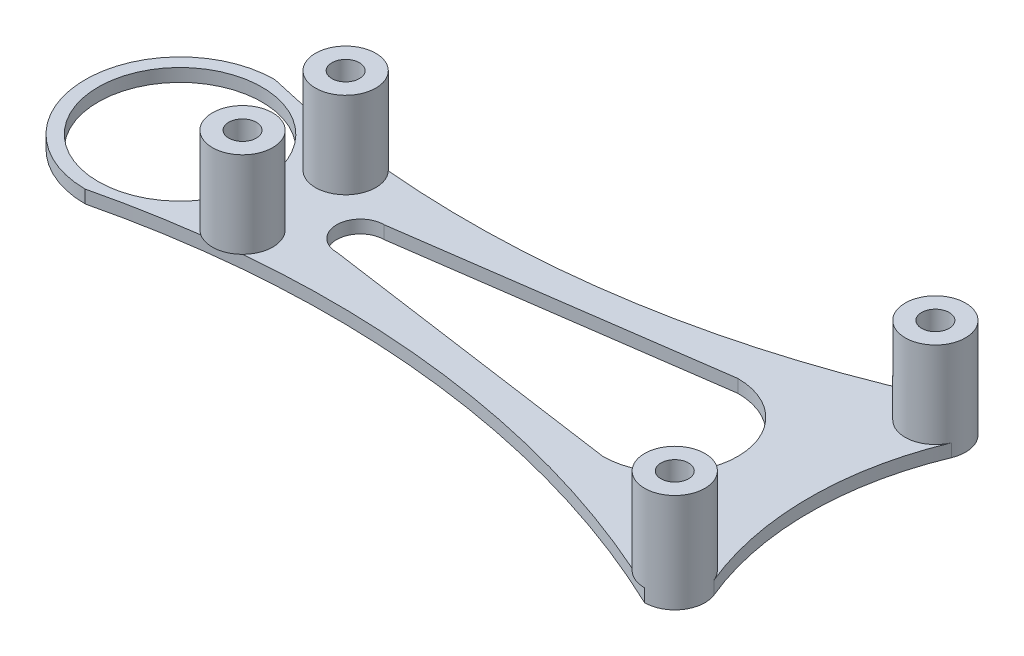
SolidWorks part; units mm, degrees
material "ABS"
ref_plane "Plano frontal" through (0, 0, 0) normal (0, 0, 1) x (1, 0, 0)
ref_plane "Plano superior" through (0, 0, 0) normal (0, 1, 0) x (1, 0, 0)
ref_plane "Plano direito" through (0, 0, 0) normal (1, 0, 0) x (0, 0, -1)
sketch "Esboço1" plane through (0, 0, 0) normal (0, 1, 0) x (1, 0, 0)
  line L0 (0, 43) -> (0, -43) construction
  line L1 (0, -43) -> (43, 0) construction
  line L2 (43, 0) -> (0, 43) construction
  line L3 (0, 43) -> (-43, 0) construction
  line L4 (-43, 0) -> (0, -43) construction
  line L5 (-43, 0) -> (43, 0) construction
  line L6 (0, 0) -> (-39.7268, 16.4554) construction
  line L7 (0, 0) -> (-39.7268, -16.4554) construction
  circle A0 centre (0, 0) radius 43 construction
  arc A1 (-33.2597, 13.7766) -> (-33.2597, -13.7766) centre (0, 0) ccw
  arc A2 (-109, 11) -> (-109, -11) centre (-109, 0) ccw
  circle A3 centre (-36.4932, 15.116) radius 1.6
  circle A4 centre (-36.4932, -15.116) radius 1.6
  arc A5 (-33.2597, 13.7766) -> (-36.4932, 18.616) centre (-36.4932, 15.116) ccw
  circle A6 centre (-95.79, 6) radius 1.6
  arc A7 (-109, 11) -> (-36.4932, 18.616) centre (-83.4775, 116.9698) ccw
  arc A8 (-109, -11) -> (-36.4932, -18.616) centre (-83.4775, -116.9698) cw
  circle A9 centre (-95.79, -5.96) radius 1.6
  arc A10 (-36.4932, -18.616) -> (-33.2597, -13.7766) centre (-36.4932, -15.116) ccw
  dimension "D1" = 86
  dimension "D4" = 7
  dimension "D5" = 22
  dimension "D9" = 3.2
  dimension "D10" = 7
  dimension "D11" = 109
  dimension "D7" = 3.2
  dimension "D8" = 13.21
  dimension "D12" = 11.96
  dimension "D13" = 6
  dimension "D2" = 22.5
  dimension "D3" = 22.5
  dimension "D6" = 109
extrude "Ressalto-extrusão1" add sketch "Esboço1" along normal mid plane 1.5
sketch "Esboço2" plane through (0, 0.75, 0) normal (0, 1, 0) x (1, 0, 0)
  line L0 (-88.0784, 2.7576) -> (-52.1196, 7.8315)
  line L2 (-88.0784, -2.7576) -> (-52.1196, -7.8315)
  arc A0 (-52.1196, -7.8315) -> (-52.1196, 7.8315) centre (-52.1196, 0) ccw
  arc A1 (-88.0784, 2.7576) -> (-88.0784, -2.7576) centre (-88.0784, 0) ccw
  circle A2 centre (-109, 0) radius 9.5
  arc A3 (-109, 11) -> (-109, -11) centre (-109, 0) ccw construction
  point P7 (-120, 0)
  point P26 (-109, 0)
  dimension "D1" = 7.8315
  dimension "D2" = 2.7576
  dimension "D6" = 19
  dimension "D7" = 11
  dimension "D3" = 18.86
  dimension "D4" = 54.8188
  dimension "D5" = 13.7766
extrude "Corte-extrusão1" cut sketch "Esboço2" against normal up to next
sketch "Esboço3" plane through (0, 0.75, 0) normal (0, 1, 0) x (1, 0, 0)
  circle A0 centre (-36.4932, 15.116) radius 3.5
  circle A1 centre (-36.4932, 15.116) radius 1.6
  circle A2 centre (-36.4932, -15.116) radius 1.6
  circle A3 centre (-36.4932, -15.116) radius 3.5
  circle A4 centre (-95.79, -5.96) radius 1.6
  circle A5 centre (-95.79, -5.96) radius 3.5
  circle A6 centre (-95.79, 6) radius 1.6
  circle A7 centre (-95.79, 6) radius 3.5
  dimension "D1" = 7
  dimension "D2" = 3.2
  dimension "D3" = 3.2
  dimension "D4" = 7
  dimension "D5" = 3.2
  dimension "D6" = 7
  dimension "D7" = 3.2
  dimension "D8" = 7
extrude "Ressalto-extrusão2" add sketch "Esboço3" along normal blind 10
